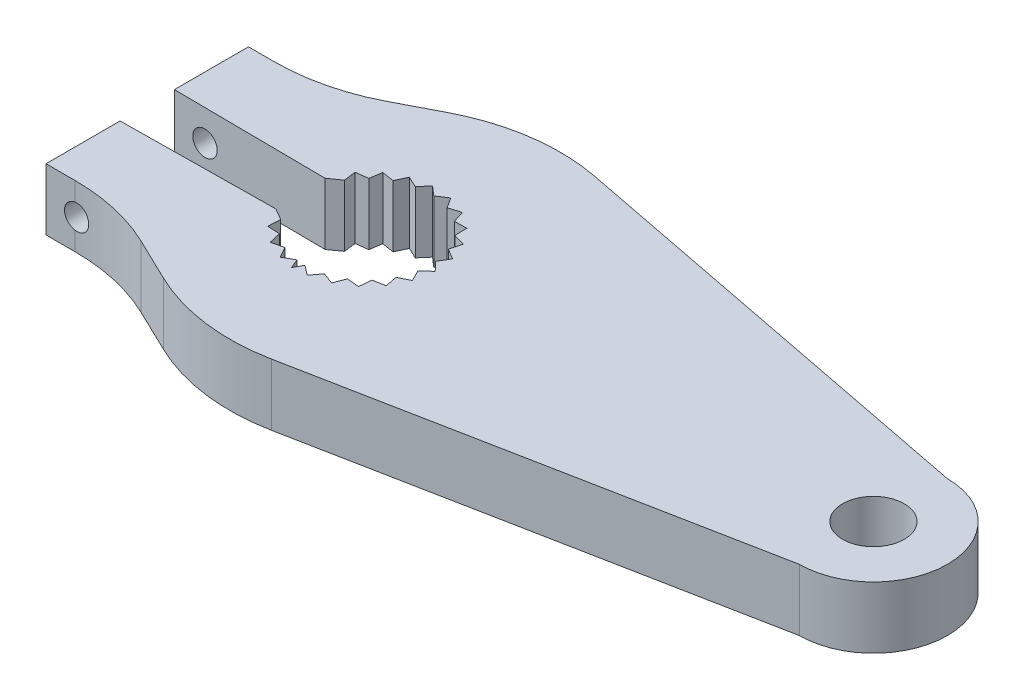
SolidWorks part; units mm, degrees
ref_plane "Front Plane" through (0, 0, 0) normal (0, 0, 1) x (1, 0, 0)
ref_plane "Top Plane" through (0, 0, 0) normal (0, 1, 0) x (1, 0, 0)
ref_plane "Right Plane" through (0, 0, 0) normal (1, 0, 0) x (0, 0, -1)
sketch "Sketch1" plane through (0, 0, 0) normal (0, 1, 0) x (1, 0, 0)
  line L0 (-25.1728, -2.8548) -> (-23.9794, -3.5543)
  line L1 (-24.0454, -4.8148) -> (-22.785, -4.8808)
  line L2 (-23.9794, -3.5543) -> (-24.0454, -4.8148)
  line L3 (-24.3704, 4.4907) -> (-24.2166, 3.2379)
  line L4 (-24.2166, 3.2379) -> (-25.3784, 2.4127)
  line L5 (-23.1176, 4.6445) -> (-24.3704, 4.4907)
  line L6 (-21.1402, 6.8376) -> (-21.6736, 5.6937)
  line L7 (-22.9202, 5.8911) -> (-23.1176, 4.6445)
  line L8 (-21.6736, 5.6937) -> (-22.9202, 5.8911)
  line L9 (-19.9963, 6.3042) -> (-21.1402, 6.8376)
  line L10 (-17.1572, 7.1161) -> (-18.2157, 6.4287)
  line L11 (-19.1682, 7.2567) -> (-19.9963, 6.3042)
  line L12 (-18.2157, 6.4287) -> (-19.1682, 7.2567)
  line L13 (-16.4697, 6.0576) -> (-17.1572, 7.1161)
  line L14 (-13.6318, 5.2416) -> (-14.8937, 5.2196)
  line L15 (-15.2627, 6.4266) -> (-16.4697, 6.0576)
  line L16 (-14.8937, 5.2196) -> (-15.2627, 6.4266)
  line L17 (-11.6354, 1.7838) -> (-12.7173, 2.4338)
  line L18 (-12.3906, 3.653) -> (-13.6097, 3.9796)
  line L19 (-12.7173, 2.4338) -> (-12.3906, 3.653)
  line L20 (-13.6097, 3.9796) -> (-13.6318, 5.2416)
  line L21 (-11.7747, -2.2065) -> (-12.3477, -1.082)
  line L22 (-11.4247, -0.2212) -> (-12.2854, 0.7019)
  line L23 (-12.3477, -1.082) -> (-11.4247, -0.2212)
  line L24 (-12.2854, 0.7019) -> (-11.6354, 1.7838)
  line L25 (-14.0075, -5.5167) -> (-13.8974, -4.2593)
  line L26 (-12.6585, -4.0185) -> (-12.8993, -2.7795)
  line L27 (-13.8974, -4.2593) -> (-12.6585, -4.0185)
  line L28 (-12.8993, -2.7795) -> (-11.7747, -2.2065)
  line L29 (-17.655, -7.1407) -> (-16.8954, -6.1327)
  line L30 (-15.7171, -6.585) -> (-15.2648, -5.4067)
  line L31 (-16.8954, -6.1327) -> (-15.7171, -6.585)
  line L32 (-15.2648, -5.4067) -> (-14.0075, -5.5167)
  line L33 (-18.663, -6.3811) -> (-17.655, -7.1407)
  line L34 (-19.5555, -6.3187) -> (-19.1458, -7.2846)
  line L35 (-18.663, -6.3811) -> (-19.1458, -7.2846)
  line L36 (-22.5011, -6.1106) -> (-21.2713, -5.8267)
  line L37 (-20.6594, -6.9306) -> (-19.5555, -6.3187)
  line L38 (-21.2713, -5.8267) -> (-20.6594, -6.9306)
  line L39 (-22.785, -4.8808) -> (-22.5011, -6.1106)
  line L40 (-41.027, 2.5576) -> (-25.3784, 2.4127)
  line L41 (-41.027, -3.0304) -> (-25.1728, -2.8548)
  line L42 (-41.027, -10.6504) -> (-41.027, -3.0304)
  line L43 (-41.027, 2.5576) -> (-41.027, 10.1776)
  line L44 (-41.027, 10.1776) -> (-38.3556, 10.1776)
  line L45 (-41.027, -10.6504) -> (-38.0435, -10.6504)
  line L46 (-29.2294, -12.6616) -> (-24.7442, -14.8208)
  line L47 (-12.0387, -16.4559) -> (33.407, -7.5885)
  line L48 (33.407, 7.6515) -> (-11.7149, 16.4559)
  line L49 (-24.9495, 14.5567) -> (-29.0126, 12.4529)
  arc A0 (33.407, -7.5885) -> (33.407, 7.6515) centre (33.407, 0.0315) ccw
  arc A1 (-24.7442, -14.8208) -> (-12.0387, -16.4559) centre (-15.9301, 3.488) ccw
  arc A2 (-11.7149, 16.4559) -> (-24.9495, 14.5567) centre (-15.6064, -3.488) ccw
  arc A3 (-38.3556, 10.1776) -> (-29.0126, 12.4529) centre (-38.3556, 30.4976) ccw
  arc A4 (-29.2294, -12.6616) -> (-38.0435, -10.6504) centre (-38.0435, -30.9704) ccw
  point P21 (-18.663, 0.0316)
  point P45 (33.407, 0.0315)
extrude "Boss-Extrude1" add sketch "Sketch1" along normal blind 6.35
sketch "Sketch2" plane through (0, 6.35, 0) normal (0, 1, 0) x (1, 0, 0)
  circle A0 centre (33.407, 0.0315) radius 3.175
  point P2 (0, 0)
  dimension "D1" = 6.35
extrude "Cut-Extrude1" cut sketch "Sketch2" against normal up to next
sketch "Sketch3" plane through (0, 0, 0) normal (0, 0, 1) x (1, 0, 0)
  line L0 (-37.852, 3.175) -> (-41.027, 3.175) construction
  line L1 (-41.027, 6.35) -> (-41.027, 0) construction
  line L2 (-37.852, 3.175) -> (-37.852, 6.35) construction
  line L3 (-29.2294, 6.35) -> (-38.0435, 6.35) construction
  circle A0 centre (-37.852, 3.175) radius 1.27
  point P2 (-37.852, 3.175)
  dimension "D1" = 2.54
extrude "Cut-Extrude2" cut sketch "Sketch3" against normal through all both and the other way through all
